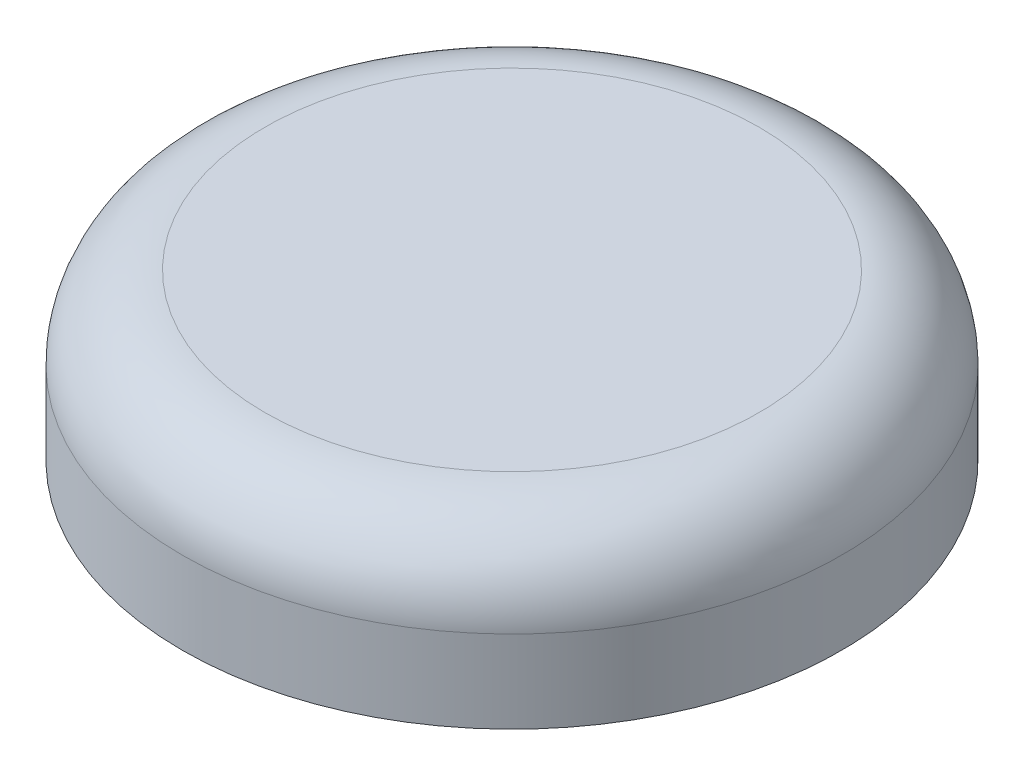
SolidWorks part; units mm, degrees
ref_plane "Front Plane" through (0, 0, 0) normal (0, 0, 1) x (1, 0, 0)
ref_plane "Top Plane" through (0, 0, 0) normal (0, 1, 0) x (1, 0, 0)
ref_plane "Right Plane" through (0, 0, 0) normal (1, 0, 0) x (0, 0, -1)
sketch "Sketch1" plane through (0, 0, 0) normal (0, 1, 0) x (1, 0, 0)
  circle A0 centre (0, 0) radius 20
  dimension "D1" = 40
extrude "Boss-Extrude1" add sketch "Sketch1" along normal blind 10
fillet "Fillet1" radius 5 1 edges at (0, 10, 20)
sketch "Sketch2" plane through (0, 0, 0) normal (0, -1, 0) x (1, 0, 0)
  circle A0 centre (0, 0) radius 10
  dimension "D1" = 20
extrude "Cut-Extrude1" cut sketch "Sketch2" against normal blind 5
